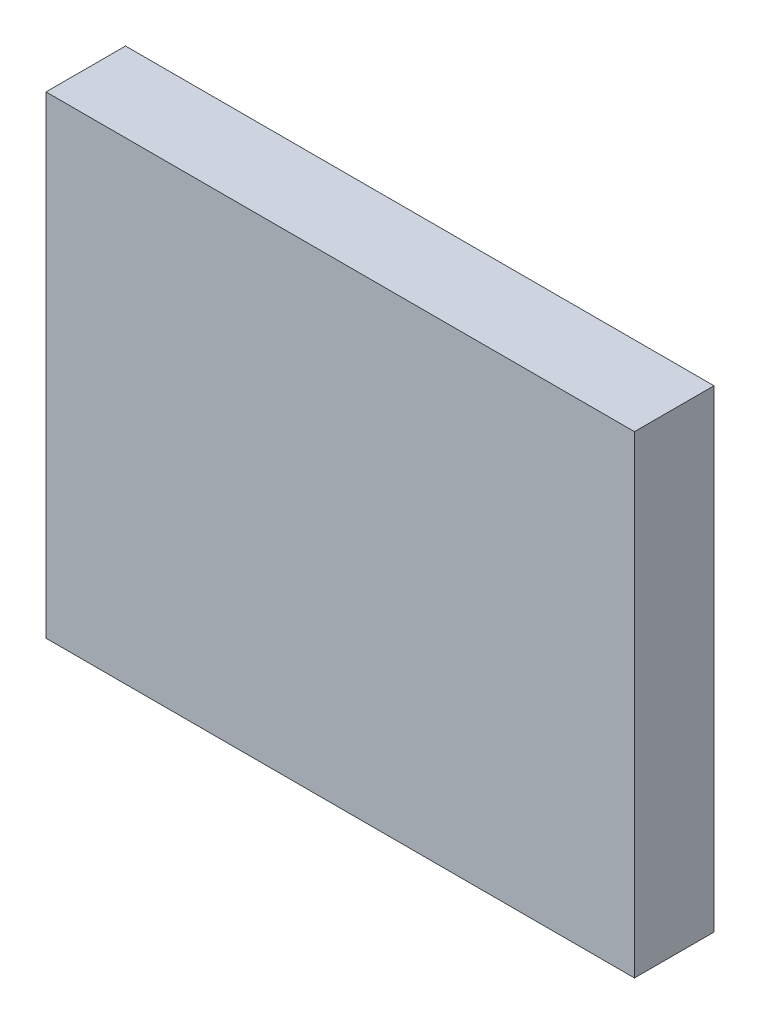
SolidWorks part; units mm, degrees
material "Бетон М200"
ref_plane "Спереди" through (0, 0, 0) normal (0, 0, 1) x (1, 0, 0)
ref_plane "Сверху" through (0, 0, 0) normal (0, 1, 0) x (1, 0, 0)
ref_plane "Справа" through (0, 0, 0) normal (1, 0, 0) x (0, 0, -1)
sketch "Эскиз1" plane through (0, 0, 0) normal (0, 0, 1) x (1, 0, 0)
  line L1 (-740, 1190) -> (740, 1190)
  line L2 (-740, 1190) -> (-740, 0)
  line L3 (-740, 0) -> (740, 0)
  line L4 (740, 1190) -> (740, 0)
  point P4 (0, 0)
  dimension "D1" = 1480
  dimension "D2" = 1190
extrude "Бобышка-Вытянуть1" add sketch "Эскиз1" along normal blind 200
